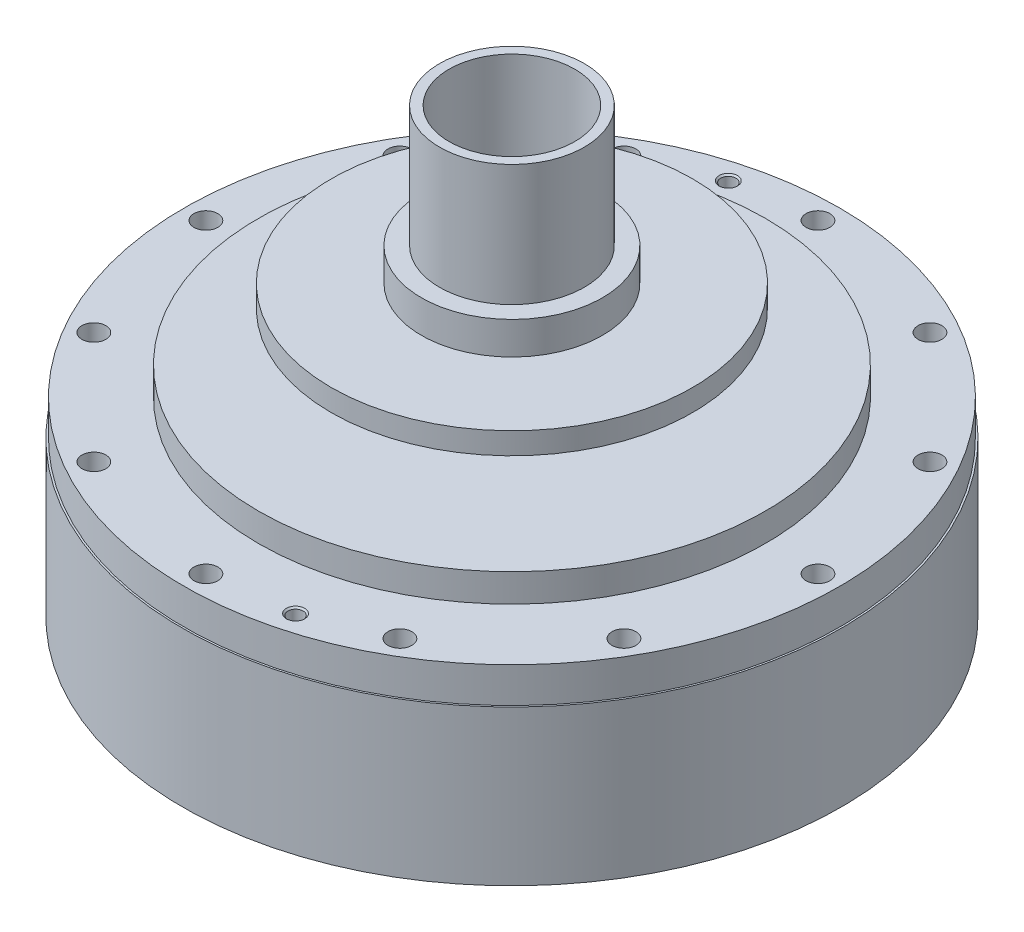
SolidWorks part; units mm, degrees
ref_plane "Front Plane" through (0, 0, 0) normal (0, 0, 1) x (1, 0, 0)
ref_plane "Top Plane" through (0, 0, 0) normal (0, 1, 0) x (1, 0, 0)
ref_plane "Right Plane" through (0, 0, 0) normal (1, 0, 0) x (0, 0, -1)
sketch "Sketch1" plane through (0, 0, 0) normal (1, 0, 0) x (0, 0, -1)
  line L0 (-17.35, 0) -> (-70, 0)
  line L1 (-70, 0) -> (-70, 5.36)
  line L2 (-70, 5.36) -> (-91, 5.36)
  line L3 (-91, 5.36) -> (-91, 48.12)
  line L4 (-91, 48.12) -> (-90.5, 48.12)
  line L5 (-90.5, 48.12) -> (-90.5, 57.86)
  line L6 (-90.5, 57.86) -> (-70, 57.86)
  line L7 (-70, 57.86) -> (-70, 65.62)
  line L8 (-70, 65.62) -> (-29.6, 65.62)
  line L9 (-29.6, 65.62) -> (-29.6, 79.12)
  line L10 (-29.6, 79.12) -> (-49.91, 79.12)
  line L11 (-49.91, 79.12) -> (-49.91, 85.12)
  line L12 (-49.91, 85.12) -> (-25, 85.12)
  line L26 (0, -94.12) -> (0, 155.7257) construction
  line L29 (-25, 85.12) -> (-25, 94.12)
  line L30 (-25, 94.12) -> (-20, 94.12)
  line L31 (-20, 94.12) -> (-20, 127.64)
  line L32 (-20, 127.64) -> (-17.35, 127.64)
  line L33 (-17.35, 127.64) -> (-17.35, 0)
  line L35 (-25, 87.12) -> (-27, 87.12)
  line L36 (-27, 87.12) -> (-27, 85.12)
  point P22 (-27, 86.12)
  dimension "D1" = 140
  dimension "D2" = 181
  dimension "D3" = 182
  dimension "D4" = 140
  dimension "D5" = 50
  dimension "D6" = 99.82
  dimension "D7" = 7
  dimension "D8" = 9.74
  dimension "D9" = 52.5
  dimension "D10" = 7.76
  dimension "D11" = 6
  dimension "D12" = 13.5
  dimension "D13" = 5.36
  dimension "D14" = 59.2
  dimension "D15" = 40
  dimension "D16" = 34.7
  dimension "D17" = 33.52
  dimension "D18" = 54
  dimension "D19" = 2
revolve "Revolve1" add sketch "Sketch1" angle 360 about L26
sketch "Sketch2" plane through (0, 0, 0) normal (0, -1, 0) x (1, 0, 0)
  circle A0 centre (0, 0) radius 33
  dimension "D1" = 66
extrude "Cut-Extrude1" cut sketch "Sketch2" against normal blind 5.3
sketch "Sketch3" plane through (0, 5.36, 0) normal (0, -1, 0) x (1, 0, 0)
  line L0 (0, 0) -> (-129.3834, 0) construction
  line L1 (-21.8702, -81.6207) -> (21.8702, 81.6207) construction
  line L2 (0, 0) -> (0, 84.5) construction
  circle A0 centre (0, 0) radius 84.5 construction
  circle A1 centre (-84.5, 0) radius 3.3
  circle A14 centre (-73.1791, 42.25) radius 3.3
  circle A15 centre (-42.25, 73.1791) radius 3.3
  circle A16 centre (0, 84.5) radius 3.3
  circle A17 centre (42.25, 73.1791) radius 3.3
  circle A18 centre (73.1791, 42.25) radius 3.3
  circle A19 centre (84.5, 0) radius 3.3
  circle A20 centre (73.1791, -42.25) radius 3.3
  circle A21 centre (42.25, -73.1791) radius 3.3
  circle A22 centre (0, -84.5) radius 3.3
  circle A23 centre (-42.25, -73.1791) radius 3.3
  circle A24 centre (-73.1791, -42.25) radius 3.3
  circle A25 centre (21.8702, 81.6207) radius 2.5 construction
  circle A26 centre (-21.8702, -81.6207) radius 2.5 construction
  point P31 (0, 0)
  point P34 (0, 0)
  dimension "D1" = 169
  dimension "D2" = 6.6
  dimension "D5" = 5
  dimension "D4" = 15
  dimension "D3" = 12
extrude "Cut-Extrude2" cut sketch "Sketch3" against normal through all
sketch "Sketch4" plane through (0, 0, 0) normal (0, -1, 0) x (1, 0, 0)
  line L0 (0, 0) -> (-35.2172, -131.4324) construction
  line L1 (-21.8702, -81.6207) -> (21.8702, 81.6207) construction
  circle A0 centre (0, 0) radius 58 construction
  circle A2 centre (-15.0115, -56.0237) radius 4 construction
  circle A17 centre (-50.2295, -29) radius 4 construction
  circle A18 centre (-56.0237, 15.0115) radius 4 construction
  circle A19 centre (-29, 50.2295) radius 4 construction
  circle A20 centre (15.0115, 56.0237) radius 4 construction
  circle A21 centre (50.2295, 29) radius 4 construction
  circle A22 centre (56.0237, -15.0115) radius 4 construction
  circle A23 centre (29, -50.2295) radius 4 construction
  point P23 (0, 0)
  dimension "D1" = 116
  dimension "D2" = 8
  dimension "D3" = 8
hole_wizard "M8x1.25 Tapped Hole2" positions "Sketch7" profile "Sketch8" tap size "M8x1.25" standard "ANSI Metric"
sketch "Sketch7" plane through (0, 0, 0) normal (0, -1, 0) x (-1, 0, 0)
  point P0 (15.0115, 56.0237)
  point P3 (-29, 50.2295)
  point P6 (-56.0237, 15.0115)
  point P9 (-50.2295, -29)
  point P12 (-15.0115, -56.0237)
  point P15 (29, -50.2295)
  point P18 (56.0237, -15.0115)
  point P21 (50.2295, 29)
sketch "Sketch8" plane through (-15.0115, 0, -56.0237) normal (1, 0, 0) x (0, 0, -1)
  line L0 (0, 0) -> (0, 25.7929)
  line L1 (0, 25.7929) -> (3.4, 23.75)
  line L2 (3.4, 23.75) -> (3.4, 0.625)
  line L3 (3.4, 0.625) -> (4.025, 0)
  line L5 (4.025, 0) -> (0, 0)
  line L6 (-3.4, 0.625) -> (-4.025, 0) construction
  line L10 (0, 25.7929) -> (-3.4, 23.75) construction
  line L11 (0, -6.35) -> (0, 107.95) construction
  dimension "Tap Drill Dia." = 6.8
  dimension "Tap Drill Depth" = 23.75
  dimension "Near C'Sink Dia." = 8.05
  dimension "Near C'Sink Angle" = 90
  dimension "Drill Angle" = 118
cosmetic thread "Hole Thread3" parameters "D1"=20, "D2"=8
cosmetic thread "Hole Thread4" parameters "D1"=20, "D2"=8
cosmetic thread "Hole Thread5" parameters "D1"=20, "D2"=8
cosmetic thread "Hole Thread6" parameters "D1"=20, "D2"=8
cosmetic thread "Hole Thread7" parameters "D1"=20, "D2"=8
cosmetic thread "Hole Thread8" parameters "D1"=20, "D2"=8
cosmetic thread "Hole Thread9" parameters "D1"=20, "D2"=8
cosmetic thread "Hole Thread10" parameters "D1"=20, "D2"=8
hole_wizard "M5x0.8 Tapped Hole2" positions "Sketch9" profile "Sketch10" tap size "M5x0.8" standard "ANSI Metric" end condition through all
sketch "Sketch9" plane through (0, 57.86, 0) normal (0, 1, 0) x (1, 0, 0)
  point P0 (-21.8702, 81.6207)
  point P3 (21.8702, -81.6207)
sketch "Sketch10" plane through (-21.8702, 57.86, -81.6207) normal (1, 0, 0) x (0, 0, 1)
  line L0 (0, 0) -> (0, 57.86)
  line L1 (0, 57.86) -> (2.1, 57.86)
  line L2 (2.1, 57.86) -> (2.1, 0.425)
  line L3 (2.1, 0.425) -> (2.525, 0)
  line L5 (2.525, 0) -> (0, 0)
  line L6 (-2.1, 0.425) -> (-2.525, 0) construction
  line L11 (0, -6.35) -> (0, 107.95) construction
  dimension "Thru Tap Drill Dia." = 4.2
  dimension "Thru Tap Drill Depth" = 57.86
  dimension "Near C'Sink Dia." = 5.05
  dimension "Near C'Sink Angle" = 90
cosmetic thread "Hole Thread11"
cosmetic thread "Hole Thread12"
